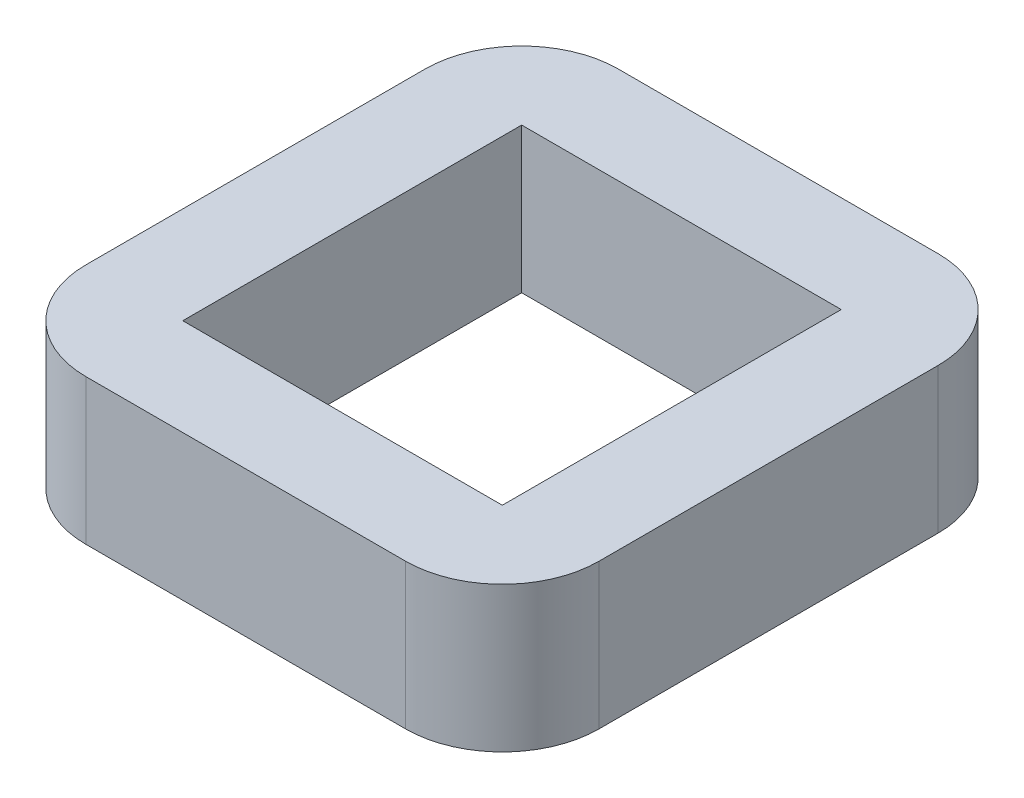
SolidWorks part; units mm, degrees
ref_plane "前基準面" through (0, 0, 0) normal (0, 0, 1) x (1, 0, 0)
ref_plane "上基準面" through (0, 0, 0) normal (0, 1, 0) x (1, 0, 0)
ref_plane "右基準面" through (0, 0, 0) normal (1, 0, 0) x (0, 0, -1)
sketch "草圖1" plane through (0, 0, 0) normal (0, 1, 0) x (1, 0, 0)
  line L0 (-16.5, 17.5) -> (-26.5, 17.5) construction
  line L1 (16.5, -17.5) -> (-16.5, -17.5)
  line L2 (16.5, -17.5) -> (16.5, 17.5)
  line L3 (16.5, 17.5) -> (-16.5, 17.5)
  line L4 (-16.5, -17.5) -> (-16.5, 17.5)
  line L5 (0, 17.5) -> (0, -17.5) construction
  line L6 (16.5, 0) -> (-16.5, 0) construction
  line L7 (16.5, -27.5) -> (-16.5, -27.5)
  line L8 (26.5, -17.5) -> (26.5, 17.5)
  line L9 (16.5, 27.5) -> (-16.5, 27.5)
  line L10 (-26.5, -17.5) -> (-26.5, 17.5)
  line L11 (0, 27.5) -> (0, -27.5) construction
  line L12 (26.5, 0) -> (-26.5, 0) construction
  line L13 (-16.5, 17.5) -> (-16.5, 27.5) construction
  line L14 (16.5, 17.5) -> (16.5, 27.5) construction
  line L15 (16.5, 17.5) -> (26.5, 17.5) construction
  arc A0 (-26.5, 17.5) -> (-16.5, 27.5) centre (-16.5, 17.5) cw
  arc A1 (16.5, 27.5) -> (26.5, 17.5) centre (16.5, 17.5) cw
  arc A2 (-26.5, -17.5) -> (-16.5, -27.5) centre (-16.5, -17.5) ccw
  arc A3 (16.5, -27.5) -> (26.5, -17.5) centre (16.5, -17.5) ccw
  point P0 (0, 0)
  point P4 (0, 0)
  dimension "D1" = 33
  dimension "D2" = 35
extrude "填料-伸長1" add sketch "草圖1" along normal blind 15
